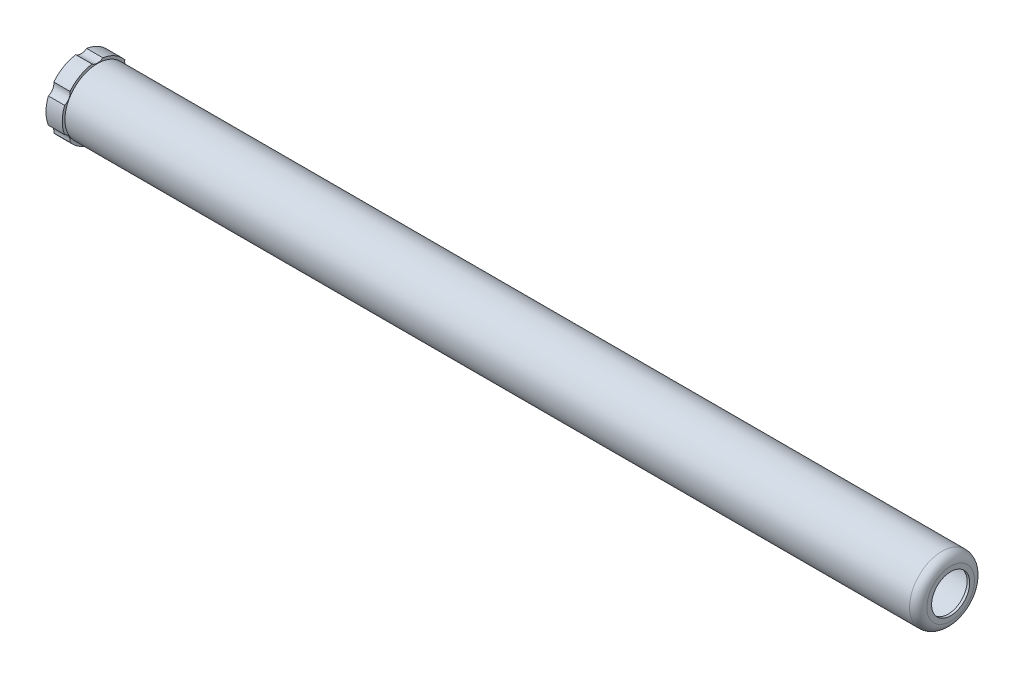
SolidWorks part; units mm, degrees
material "6061 Alloy"
ref_plane "Front Plane" through (0, 0, 0) normal (0, 0, 1) x (1, 0, 0)
ref_plane "Top Plane" through (0, 0, 0) normal (0, 1, 0) x (1, 0, 0)
ref_plane "Right Plane" through (0, 0, 0) normal (1, 0, 0) x (0, 0, -1)
sketch "Sketch1" plane through (0, 0, 0) normal (0, 0, 1) x (1, 0, 0)
  line L0 (-5.08, 17.526) -> (-500.634, 17.526)
  line L1 (-500.634, 17.526) -> (-500.634, 19.05)
  line L2 (-500.634, 19.05) -> (-5.08, 19.05)
  line L6 (0, 13.97) -> (0, 11.176)
  line L7 (-1.524, 13.97) -> (-1.524, 11.176)
  line L8 (-1.524, 11.176) -> (0, 11.176)
  line L9 (-484.8283, 0) -> (0, 0) construction
  arc A2 (-5.08, 19.05) -> (0, 13.97) centre (-5.08, 13.97) cw
  arc A3 (-5.08, 17.526) -> (-1.524, 13.97) centre (-5.08, 13.97) cw
  point P3 (3.6747, -3.6728)
  point P10 (0, 0)
  point P12 (0, 0)
  point P15 (0, 0)
  point P16 (0, 0)
  point P17 (0, 0)
  dimension "D1" = 500.634
  dimension "D4" = 5.08
  dimension "D2" = 19.05
  dimension "D3" = 1.524
  dimension "D5" = 6.35
revolve "Revolve1" add sketch "Sketch1" angle 360 about L9
sketch "Sketch2" plane through (-500.634, 0, 0) normal (-1, 0, 0) x (0, 0, 1)
  circle A0 centre (0, 0) radius 20.6375
  circle A1 centre (0, 0) radius 15.875
  dimension "D1" = 41.275
  dimension "D2" = 31.75
extrude "Boss-Extrude1" add sketch "Sketch2" along normal blind 9.525
sketch "Sketch4" plane through (-510.159, 0, 0) normal (-1, 0, 0) x (0, 0, 1)
  circle A0 centre (0, 0) radius 20.6375 construction
  arc A1 (3.175, 20.3918) -> (-3.175, 20.3918) centre (0, 0) ccw
  arc A2 (-3.175, 20.3918) -> (3.175, 20.3918) centre (0, 24.3574) ccw
  arc A3 (19.2473, 7.4463) -> (16.0723, 12.9455) centre (0, 0) ccw
  arc A4 (16.0723, 12.9455) -> (19.2473, 7.4463) centre (21.0941, 12.1787) ccw
  arc A5 (16.0723, -12.9455) -> (19.2473, -7.4463) centre (0, 0) ccw
  arc A6 (19.2473, -7.4463) -> (16.0723, -12.9455) centre (21.0941, -12.1787) ccw
  arc A7 (-3.175, -20.3918) -> (3.175, -20.3918) centre (0, 0) ccw
  arc A8 (3.175, -20.3918) -> (-3.175, -20.3918) centre (0, -24.3574) ccw
  arc A9 (-19.2473, -7.4463) -> (-16.0723, -12.9455) centre (0, 0) ccw
  arc A10 (-16.0723, -12.9455) -> (-19.2473, -7.4463) centre (-21.0941, -12.1787) ccw
  arc A11 (-16.0723, 12.9455) -> (-19.2473, 7.4463) centre (0, 0) ccw
  arc A12 (-19.2473, 7.4463) -> (-16.0723, 12.9455) centre (-21.0941, 12.1787) ccw
  point P23 (0, 0)
  dimension "D1" = 6.35
  dimension "D2" = 5.08
  dimension "D3" = 6
extrude "Cut-Extrude1" cut sketch "Sketch4" against normal through all and the other way through all
